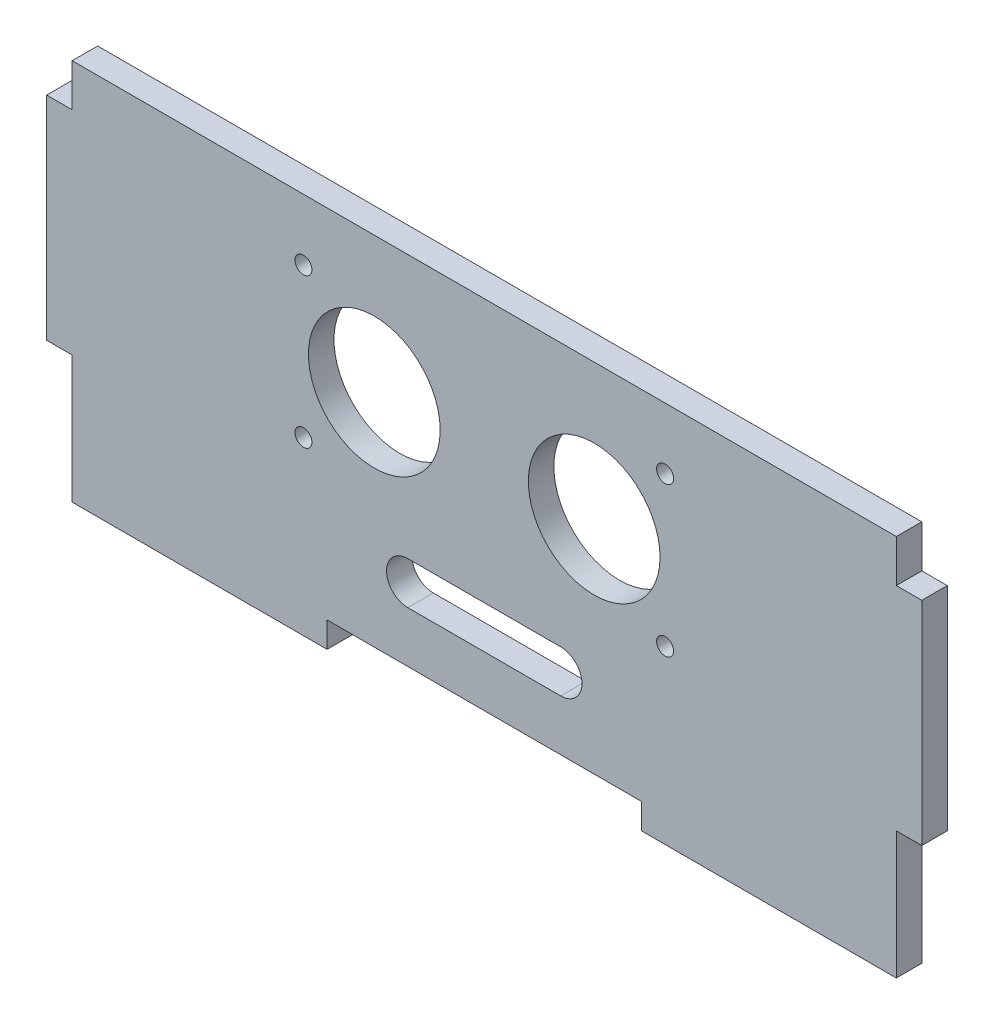
SolidWorks part; units mm, degrees
ref_plane "Plano frontal" through (0, 0, 0) normal (0, 0, 1) x (1, 0, 0)
ref_plane "Plano superior" through (0, 0, 0) normal (0, 1, 0) x (1, 0, 0)
ref_plane "Plano direito" through (0, 0, 0) normal (1, 0, 0) x (0, 0, -1)
sketch "Esboço1" plane through (0, 0, 0) normal (0, 0, 1) x (1, 0, 0)
  line L1 (-51.5, -27.5) -> (51.5, -27.5)
  line L2 (-51.5, -27.5) -> (-51.5, 27.5)
  line L3 (-51.5, 27.5) -> (51.5, 27.5)
  line L4 (51.5, -27.5) -> (51.5, 27.5)
  line L5 (-51.5, -27.5) -> (51.5, 27.5) construction
  line L6 (-51.5, 27.5) -> (51.5, -27.5) construction
  point P0 (0, 0)
  dimension "D1" = 55
  dimension "D2" = 103
extrude "Ressalto-extrusão1" add sketch "Esboço1" along normal blind 3
sketch "Esboço2" plane through (0, 0, 0) normal (0, 0, -1) x (-1, 0, 0)
  line L0 (51.5, -27.5) -> (-51.5, -27.5) construction
  line L1 (-51.5, 27.5) -> (-48.5, 27.5)
  line L2 (-51.5, 27.5) -> (-51.5, -27.5)
  line L3 (-51.5, -27.5) -> (-48.5, -27.5)
  line L4 (-48.5, 27.5) -> (-48.5, -27.5)
  line L5 (-51.5, 12.5) -> (-48.5, 12.5)
  line L6 (51.5, 27.5) -> (48.5, 27.5)
  line L7 (51.5, 27.5) -> (51.5, -27.5)
  line L8 (51.5, -27.5) -> (48.5, -27.5)
  line L9 (48.5, 27.5) -> (48.5, -27.5)
  line L10 (-51.5, -12.5) -> (-48.5, -12.5)
  line L11 (48.5, 12.5) -> (51.5, 12.5)
  line L12 (48.5, -12.5) -> (51.5, -12.5)
  line M8 (-51.5, 27.5) -> (-51.5, -27.5)
  line M9 (-51.5, -27.5) -> (51.5, -27.5)
  line M10 (51.5, -27.5) -> (51.5, 27.5)
  line M11 (51.5, 27.5) -> (-51.5, 27.5)
  dimension "D1" = 3
  dimension "D2" = 15
  dimension "D3" = 15
extrude "Corte-extrusão1" cut sketch "Esboço2" against normal through all contours L5 L4 M8 M11 | L10 L4 M8 M9 | L9 L11 L7 M11 | L12 L9 M9 M10
sketch "Esboço3" plane through (0, 0, 0) normal (0, 0, -1) x (-1, 0, 0)
  line L0 (48.5, -12.5) -> (48.5, -27.5) construction
  line L1 (-48.5, -27.5) -> (48.5, -27.5)
  line L2 (-48.5, -27.5) -> (-48.5, -24.5)
  line L3 (-48.5, -24.5) -> (48.5, -24.5)
  line L4 (48.5, -27.5) -> (48.5, -24.5)
  line L5 (-18.5, -24.5) -> (-18.5, -27.5)
  line L6 (18.5, -24.5) -> (18.5, -27.5)
  dimension "D1" = 3
  dimension "D2" = 30
  dimension "D3" = 30
extrude "Corte-extrusão2" cut sketch "Esboço3" against normal through all contours L6 L3 L5 L1
sketch "Esboço4" plane through (0, 0, 0) normal (0, 0, -1) x (-1, 0, 0)
  line L0 (48.5, 27.5) -> (48.5, 12.5) construction
  line L1 (-48.5, 27.5) -> (48.5, 27.5)
  line L2 (-48.5, 27.5) -> (-48.5, 17.5)
  line L3 (-48.5, 17.5) -> (48.5, 17.5)
  line L4 (48.5, 27.5) -> (48.5, 17.5)
  dimension "D1" = 10
extrude "Corte-extrusão3" cut sketch "Esboço4" against normal blind 10
sketch "Esboço5" plane through (0, 0, 3) normal (0, 0, 1) x (1, 0, 0)
  line L0 (0, 0) -> (0, 36.689) construction
  line L1 (-12.94, 1.5) -> (12.94, 1.5) construction
  line L2 (48.5, 17.5) -> (-48.5, 17.5) construction
  circle A0 centre (-12.94, 1.5) radius 7.75
  circle A1 centre (12.94, 1.5) radius 7.75
  point P2 (-12.94, 1.5)
  point P4 (0, 0)
  point P10 (0, 1.5)
  point P11 (0, 10.1613)
  point P12 (0, 0)
  point P14 (13.2607, 1.5)
  dimension "D1" = 15.5
  dimension "D2" = 16
  dimension "D4" = 25.88
extrude "Corte-extrusão4" cut sketch "Esboço5" against normal through all
sketch "Esboço6" plane through (0, 0, 0) normal (0, 0, -1) x (-1, 0, 0)
  line L0 (-18.5, -24.5) -> (18.5, -24.5) construction
  line L1 (-9, -18.5) -> (9, -18.5)
  line L2 (-9, -18.5) -> (-9, -13.5) construction
  line L3 (-9, -13.5) -> (9, -13.5)
  line L4 (9, -18.5) -> (9, -13.5) construction
  line L5 (-9, -18.5) -> (9, -13.5) construction
  line L6 (-9, -13.5) -> (9, -18.5) construction
  arc A0 (-9, -13.5) -> (-9, -18.5) centre (-9, -16) ccw
  arc A1 (9, -13.5) -> (9, -18.5) centre (9, -16) cw
  point P0 (0, -16)
  dimension "D1" = 5
  dimension "D2" = 18
  dimension "D3" = 6
extrude "Corte-extrusão5" cut sketch "Esboço6" against normal through all
sketch "Esboço10" plane through (0, 0, 0) normal (0, 0, -1) x (-1, 0, 0)
  line L0 (-12.94, 1.5) -> (12.94, 1.5) construction
  line L2 (-21.285, -7.29) -> (21.285, -7.29) construction
  line L3 (-21.285, -7.29) -> (-21.285, 10.29) construction
  line L4 (-21.285, 10.29) -> (21.285, 10.29) construction
  line L5 (21.285, -7.29) -> (21.285, 10.29) construction
  line L6 (-21.285, -7.29) -> (21.285, 10.29) construction
  line L7 (-21.285, 10.29) -> (21.285, -7.29) construction
  circle A0 centre (12.94, 1.5) radius 7.75 construction
  circle A1 centre (-12.94, 1.5) radius 7.75 construction
  circle A2 centre (12.94, 1.5) radius 7.75 construction
  circle A3 centre (-12.94, 1.5) radius 7.75 construction
  circle A4 centre (-21.285, 10.29) radius 1
  circle A5 centre (-21.285, -7.29) radius 1
  circle A6 centre (21.285, -7.29) radius 1
  circle A7 centre (21.285, 10.29) radius 1
  point P6 (0, 1.5)
  dimension "D3" = 2
  dimension "D1" = 42.57
  dimension "D2" = 17.58
extrude "Corte-extrusão6" cut sketch "Esboço10" against normal through all
